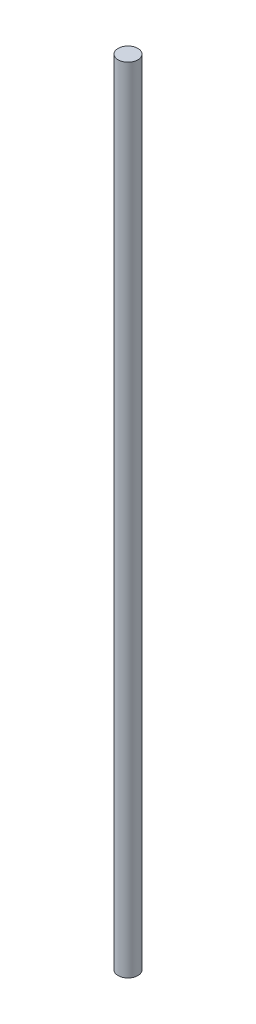
SolidWorks part; units mm, degrees
ref_plane "前视基准面" through (0, 0, 0) normal (0, 0, 1) x (1, 0, 0)
ref_plane "上视基准面" through (0, 0, 0) normal (0, 1, 0) x (1, 0, 0)
ref_plane "右视基准面" through (0, 0, 0) normal (1, 0, 0) x (0, 0, -1)
sketch "草图1" plane through (0, 0, 0) normal (0, 1, 0) x (1, 0, 0)
  circle A1 centre (0, 0) radius 10
extrude "凸台-拉伸1" add sketch "草图1" along normal blind 800
